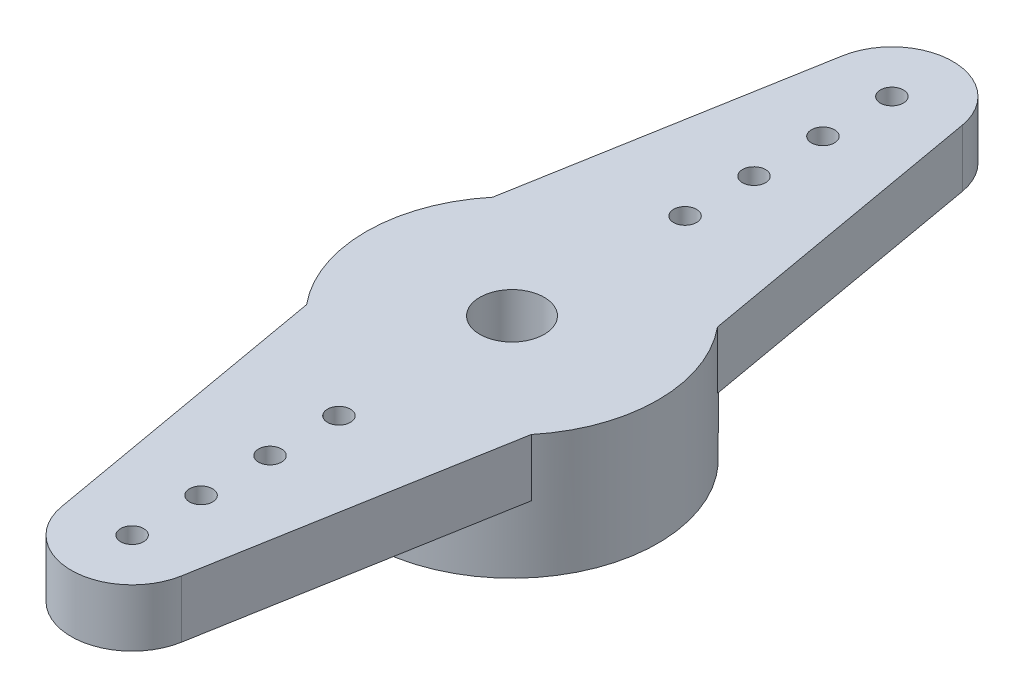
SolidWorks part; units mm, degrees
material "Polyethylene Cross-Linked"
ref_plane "Front Plane" through (0, 0, 0) normal (0, 0, 1) x (1, 0, 0)
ref_plane "Top Plane" through (0, 0, 0) normal (0, 1, 0) x (1, 0, 0)
ref_plane "Right Plane" through (0, 0, 0) normal (1, 0, 0) x (0, 0, -1)
sketch "Sketch1" plane through (0, 0, 0) normal (0, 1, 0) x (1, 0, 0)
  circle A0 centre (0, 0) radius 6.35
  dimension "D1" = 12.7
extrude "Boss-Extrude1" add sketch "Sketch1" along normal blind 5.4
sketch "Sketch2" plane through (0, 5.4, 0) normal (0, 1, 0) x (1, 0, 0)
  line L0 (0, 0) -> (0, 16.53) construction
  line L1 (-2.6097, 16.9902) -> (-4.8916, 4.049)
  line L2 (0, 19.18) -> (0, 16.53) construction
  line L3 (2.6097, 16.9902) -> (4.8916, 4.049)
  arc A0 (2.6097, 16.9902) -> (-2.6097, 16.9902) centre (0, 16.53) ccw
  arc A4 (4.8916, 4.049) -> (-4.8916, 4.049) centre (0, 0) ccw
  circle A5 centre (0, 0) radius 6.35 construction
  dimension "D1" = 5.3
  dimension "D2" = 19.18
  dimension "D3" = 10
  dimension "D4" = 9.7832
extrude "horn" add sketch "Sketch2" against normal blind 2.5
sketch "Sketch4" plane through (0, 5.4, 0) normal (0, -1, 0) x (-1, 0, 0)
  circle A0 centre (0, 0) radius 1.4
  dimension "D1" = 2.8
extrude "Cut-Extrude1" cut sketch "Sketch4" along normal through all
sketch "Sketch5" plane through (0, 0, 0) normal (0, -1, 0) x (-1, 0, 0)
  circle A0 centre (0, 16.53) radius 0.5
  dimension "D1" = 1
extrude "Cut-Extrude2" cut sketch "Sketch5" against normal through all
sketch "Sketch6" plane through (0, 0, 0) normal (0, 1, 0) x (1, 0, 0)
  line L0 (0, 0) -> (0, 16.53) construction
pattern_linear "LPattern1" count 4 spacing 3 along (0, 0, 1) of "Cut-Extrude2"
mirror "Mirror1" about plane through (0, 0, 0) normal (0, 0, 1) of "horn", "LPattern1", "Cut-Extrude2"
sketch "Sketch8" plane through (0, 0, 0) normal (0, -1, 0) x (-1, 0, 0)
  line L0 (0, -2.9) -> (0.2629, -2.5867)
  line L1 (0, -2.9) -> (-0.2629, -2.5867)
  line L2 (0, -2.6) -> (0, -2.9) construction
  line L3 (0, 0) -> (0, -2.6) construction
  arc A1 (-0.2629, -2.5867) -> (0.2629, -2.5867) centre (0, 0) ccw
  dimension "D1" = 0.3
  dimension "D2" = 5.2
  dimension "D3" = 80
sketch "Sketch10" plane through (0, 0, 0) normal (0, -1, 0) x (-1, 0, 0)
  circle A0 centre (0, 0) radius 6.35
  circle A1 centre (0, 0) radius 4.25
  circle A2 centre (0, 0) radius 6.35 construction
  dimension "D1" = 8.5
